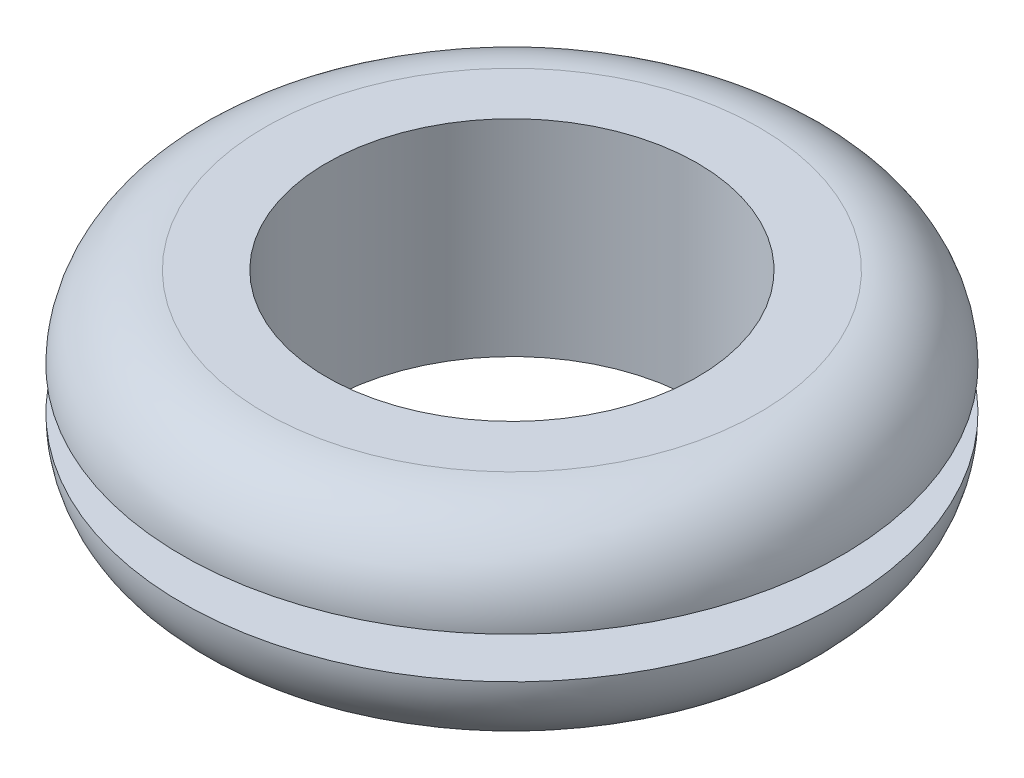
SolidWorks part; units mm, degrees
ref_plane "Front" through (0, 0, 0) normal (0, 0, 1) x (1, 0, 0)
ref_plane "Top" through (0, 0, 0) normal (0, 1, 0) x (1, 0, 0)
ref_plane "Right" through (0, 0, 0) normal (1, 0, 0) x (0, 0, -1)
sketch "Sketch1" plane through (0, 0, 0) normal (1, 0, 0) x (0, 0, -1)
  line L0 (0, -3.9688) -> (0, 3.9688) construction
  line L1 (0, 0.7937) -> (0, -0.7937) construction
  line L2 (-12.7, 3.9688) -> (12.7, 3.9688) construction
  line L3 (-7.1438, 0.7937) -> (7.1438, 0.7938) construction
  line L4 (-9.525, 0) -> (9.525, 0) construction
  point P12 (-7.1438, 0.7937)
  point P13 (7.1438, 0.7938)
  point P14 (-9.525, 0)
  point P15 (9.525, 0)
  point P16 (-12.7, 3.9688)
  point P17 (0, -3.9688)
  point P18 (12.7, 3.9688)
  point P19 (0, 3.9688)
  point P20 (0, 0.7937)
  point P21 (0, -0.7937)
  dimension "Overall Height E" = 7.9375
  dimension "Material Thickness B" = 1.5875
  dimension "Flange Diameter D" = 25.4
  dimension "ID C" = 14.2875
  dimension "For ID A" = 19.05
sketch "Sketch2" plane through (0, 0, 0) normal (1, 0, 0) x (0, 0, -1)
  line L0 (-7.1437, -3.9688) -> (-7.1437, 3.9688)
  line L1 (-7.1437, 3.9688) -> (-9.525, 3.9688)
  line L2 (-9.525, 0.7937) -> (-9.525, -0.7937)
  line L3 (-9.525, 0.7937) -> (-12.7, 0.7937)
  line L4 (-9.525, -0.7937) -> (-12.7, -0.7937)
  line L5 (-7.1437, -3.9688) -> (-9.525, -3.9688)
  arc A0 (-12.7, 0.7937) -> (-9.525, 3.9688) centre (-9.525, 0.7938) cw
  arc A1 (-12.7, -0.7937) -> (-9.525, -3.9688) centre (-9.525, -0.7938) ccw
  point P4 (-12.7, 0.7938)
revolve "Revolve1" add sketch "Sketch2" angle 360 about L0
ref_plane "Plane1" through (0, 3.9688, 0) normal (0, -1, 0) x (0, 0, -1)
sketch "Sketch3" plane through (0, 3.9688, 0) normal (0, -1, 0) x (0, 0, -1)
  line L0 (0, -12.7) -> (0, 12.7) construction
  line L1 (-12.7, 0) -> (12.7, 0) construction
  line L2 (0, 7.1438) -> (0, -7.1438) construction
  line L3 (-7.1438, 0) -> (7.1438, 0) construction
  line L4 (0, 9.525) -> (0, -9.525) construction
  line L5 (-9.525, 0) -> (9.525, 0) construction
  point P11 (0, 12.7)
  point P12 (0, 7.1438)
  point P13 (0, -7.1438)
  point P14 (0, -12.7)
  point P19 (0, -9.525)
  point P20 (0, 9.525)
